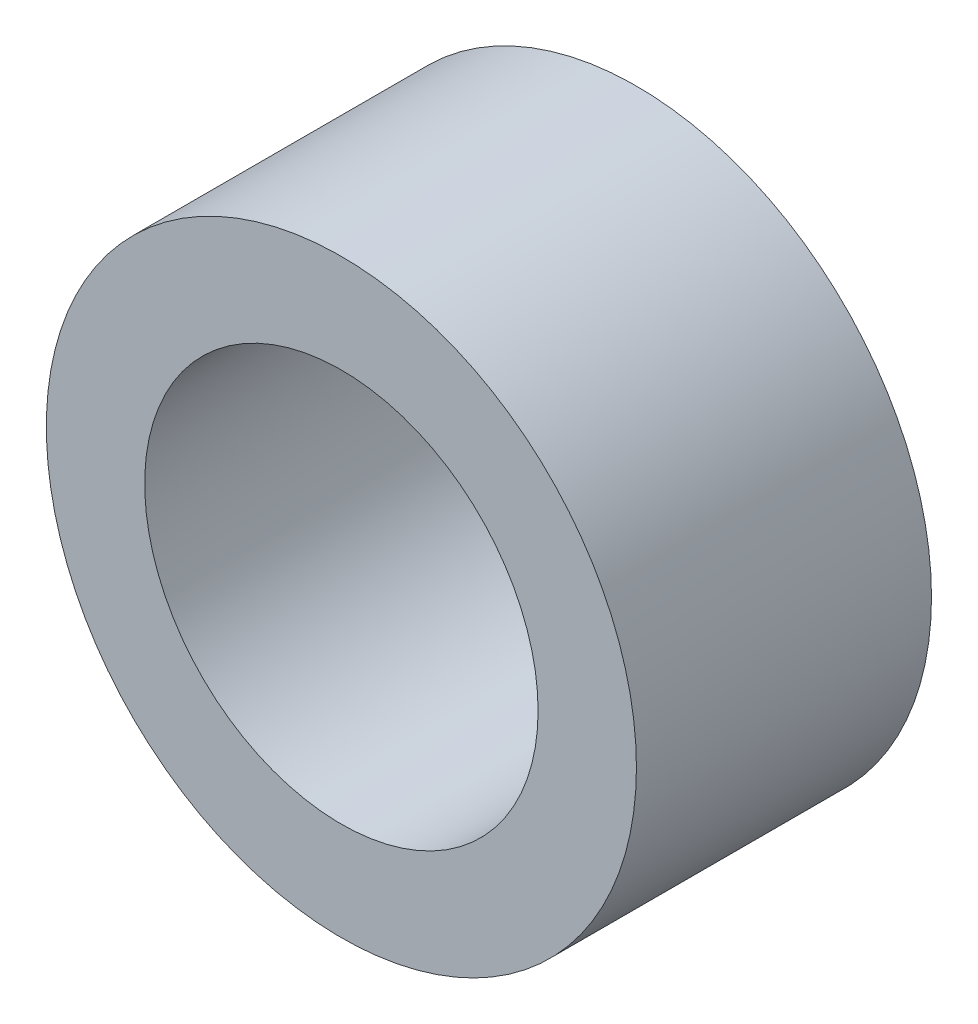
SolidWorks part; units mm, degrees
ref_plane "Front Plane" through (0, 0, 0) normal (0, 0, 1) x (1, 0, 0)
ref_plane "Top Plane" through (0, 0, 0) normal (0, 1, 0) x (1, 0, 0)
ref_plane "Right Plane" through (0, 0, 0) normal (1, 0, 0) x (0, 0, -1)
sketch "Sketch1" plane through (0, 0, 0) normal (0, 0, 1) x (1, 0, 0)
  circle A0 centre (0, 0) radius 25.4
  circle A1 centre (0, 0) radius 38.1
  dimension "D1" = 50.8
  dimension "D2" = 76.2
extrude "Boss-Extrude1" add sketch "Sketch1" against normal blind 38.1 from offset 19.05
